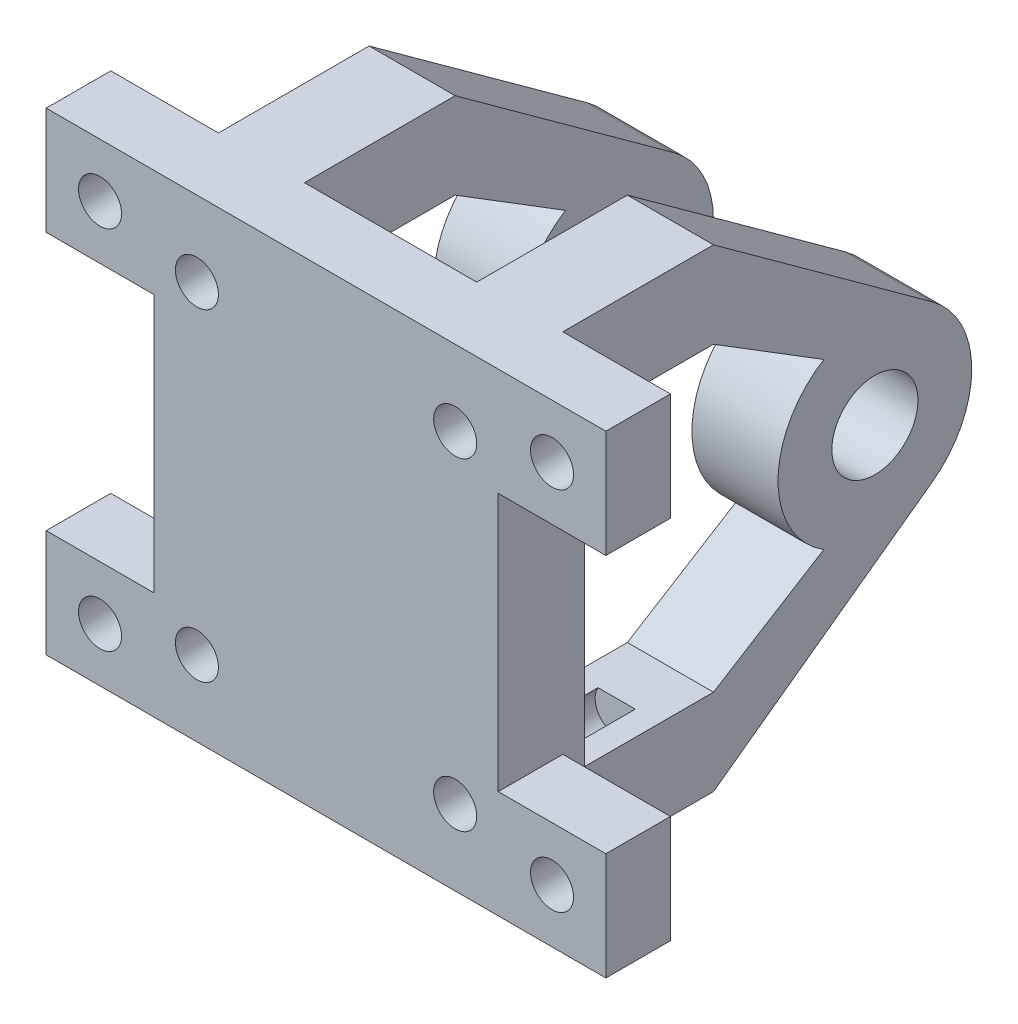
SolidWorks part; units mm, degrees
material "1060 合金"
ref_plane "前视基准面" through (0, 0, 0) normal (0, 0, 1) x (1, 0, 0)
ref_plane "上视基准面" through (0, 0, 0) normal (0, 1, 0) x (1, 0, 0)
ref_plane "右视基准面" through (0, 0, 0) normal (1, 0, 0) x (0, 0, -1)
sketch "草图1" plane through (0, 0, 0) normal (1, 0, 0) x (0, 0, -1)
  line L0 (0, 0) -> (-56.4321, 0) construction
  line L1 (5.2847, 7.285) -> (-15, 22)
  line L2 (-15, 22) -> (-35, 22)
  line L3 (-35, 22) -> (-35, -0.0255)
  line L4 (-4.7464, 7.6466) -> (-15, 14)
  line L5 (-15, 14) -> (-27, 14)
  line L6 (-27, 14) -> (-27, -14)
  line L7 (5.2847, -7.285) -> (-15, -22)
  line L8 (-15, -14) -> (-27, -14)
  line L9 (-4.7464, -7.6466) -> (-15, -14)
  line L10 (-35, -22) -> (-35, -0.0255)
  line L11 (-15, -22) -> (-35, -22)
  arc A0 (-4.7464, 7.6466) -> (-4.7464, -7.6466) centre (0, 0) ccw
  circle A1 centre (0, 0) radius 4
  arc A2 (5.2847, -7.285) -> (5.2847, 7.285) centre (0, 0) ccw
  point P19 (-27, 0)
  dimension "D1" = 18
  dimension "D2" = 8
  dimension "D3" = 8
  dimension "D4" = 8
  dimension "D5" = 22
  dimension "D6" = 35
  dimension "D7" = 20
extrude "凸台-拉伸1" add sketch "草图1" along normal mid plane 8
sketch "草图2" plane through (0, 0, 35) normal (0, 0, 1) x (1, 0, 0)
  line L0 (4, 0) -> (-4, 0) construction
  line L1 (4, 22) -> (4, -22) construction
  line L2 (-4, 22) -> (-4, -22) construction
  circle A0 centre (0, 15) radius 2
  circle A1 centre (0, -15) radius 2
  dimension "D1" = 4
  dimension "D2" = 15
extrude "切除-拉伸1" cut sketch "草图2" against normal blind 15
sketch "草图4" plane through (0, 0, 35) normal (0, 0, 1) x (1, 0, 0)
  line L0 (4, -22) -> (-4, -22) construction
  line L1 (4, 22) -> (20, 22)
  line L2 (4, 22) -> (4, -22)
  line L3 (4, -22) -> (20, -22)
  line L4 (20, 22) -> (20, -22)
  dimension "D1" = 16
extrude "凸台-拉伸2" add sketch "草图4" against normal blind 6
ref_plane "基准面1" through (12, 0, 0) normal (1, 0, 0) x (0, 0, -1)
mirror "镜向1" about plane through (12, 0, 0) normal (1, 0, 0) of "切除-拉伸1", "凸台-拉伸1"
sketch "草图5" plane through (0, 0, 35) normal (0, 0, 1) x (1, 0, 0)
  line L0 (12, 22) -> (12, -22) construction
  line L1 (-4, 22) -> (-14, 22)
  line L2 (-4, 22) -> (-4, 12)
  line L3 (-4, 12) -> (-14, 12)
  line L4 (-14, 22) -> (-14, 12)
  line L5 (28, 22) -> (-4, 22) construction
  line L6 (28, -22) -> (-4, -22) construction
  line L7 (38, 22) -> (38, 12)
  line L8 (28, 12) -> (38, 12)
  line L9 (28, 22) -> (28, 12)
  line L10 (28, 22) -> (38, 22)
  line L11 (-4, 0) -> (28, 0) construction
  line L12 (-4, 22) -> (-4, -22) construction
  line L13 (28, 22) -> (28, -22) construction
  line L14 (28, -22) -> (38, -22)
  line L15 (28, -22) -> (28, -12)
  line L16 (28, -12) -> (38, -12)
  line L17 (38, -22) -> (38, -12)
  line L18 (-14, -22) -> (-14, -12)
  line L19 (-4, -12) -> (-14, -12)
  line L20 (-4, -22) -> (-4, -12)
  line L21 (-4, -22) -> (-14, -22)
  circle A0 centre (-9, 17) radius 2
  circle A1 centre (33, 17) radius 2
  circle A2 centre (33, -17) radius 2
  circle A3 centre (-9, -17) radius 2
  point P13 (-9, 22)
  point P14 (-14, 17)
  dimension "D3" = 4
  dimension "D1" = 10
  dimension "D2" = 10
extrude "凸台-拉伸3" add sketch "草图5" against normal blind 6
ref_plane "基准面2" through (0, 0, 4) normal (0, 0, -1) x (-1, 0, 0)
sketch "草图6" plane through (0, 0, 4) normal (0, 0, -1) x (-1, 0, 0)
  circle A0 centre (0, 0) radius 1.5
  dimension "D1" = 3
extrude "切除-拉伸2" cut sketch "草图6" along normal through all
